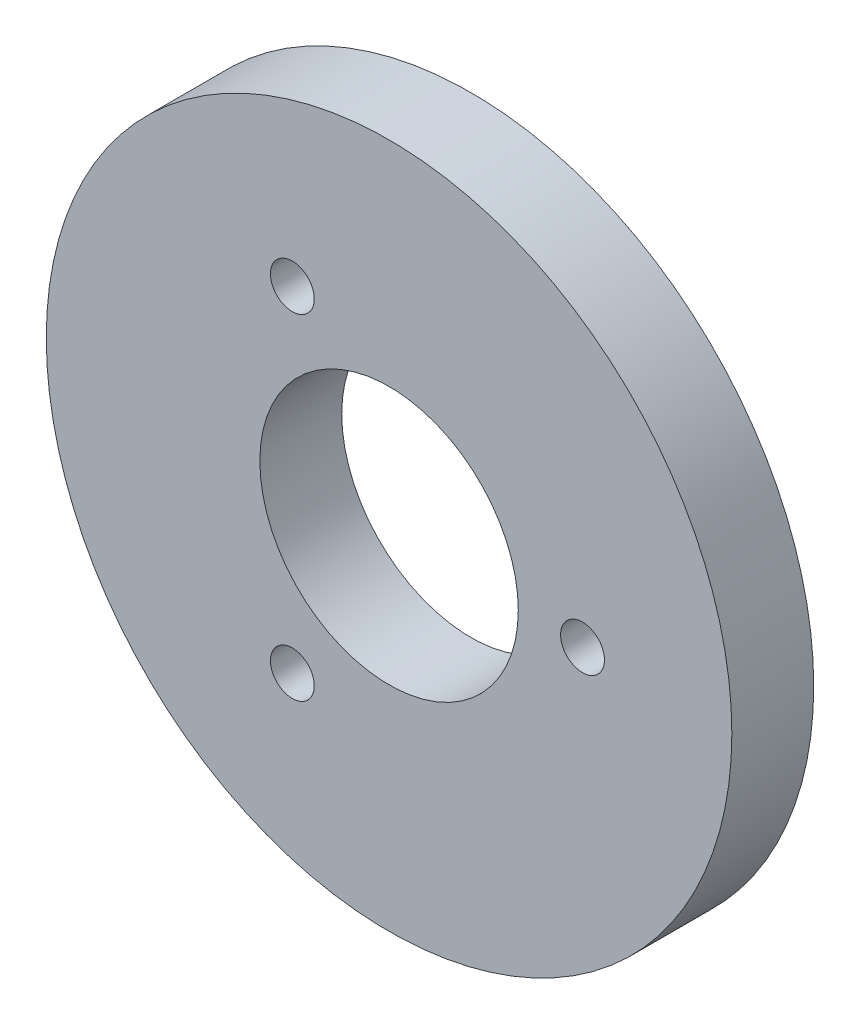
SolidWorks part; units mm, degrees
material "Acrylic (Medium-high impact)"
ref_plane "Front Plane" through (0, 0, 0) normal (0, 0, 1) x (1, 0, 0)
ref_plane "Top Plane" through (0, 0, 0) normal (0, 1, 0) x (1, 0, 0)
ref_plane "Right Plane" through (0, 0, 0) normal (1, 0, 0) x (0, 0, -1)
sketch "Sketch1" plane through (0, 0, 0) normal (0, 0, 1) x (1, 0, 0)
  circle A1 centre (107.8575, 1.2823) radius 10.0203 construction
  circle A2 centre (107.8575, 1.2823) radius 26.5811
  circle A3 centre (107.8575, 1.2823) radius 26.5811
  circle A7 centre (107.8575, 1.2823) radius 10.0203
  circle A8 centre (100.3575, -11.7081) radius 1.7 construction
  circle A9 centre (122.8575, 1.2823) radius 1.7 construction
  circle A10 centre (100.3575, 14.2727) radius 1.7 construction
  circle A11 centre (100.3575, -11.7081) radius 1.7
  circle A12 centre (122.8575, 1.2823) radius 1.7
  circle A13 centre (100.3575, 14.2727) radius 1.7
  dimension "D1" = 6.35
extrude "Boss-Extrude1" add sketch "Sketch1" along normal blind 6.35
